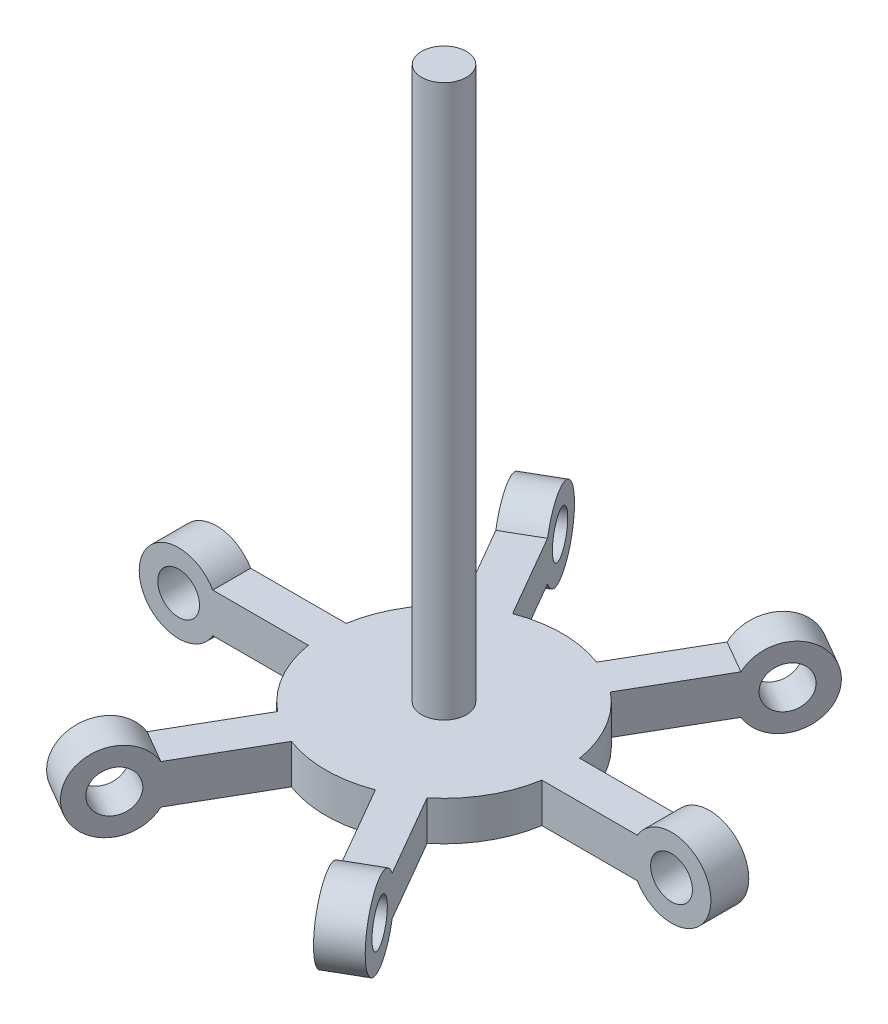
SolidWorks part; units mm, degrees
material "6061 合金"
ref_plane "前视基准面" through (0, 0, 0) normal (0, 0, 1) x (1, 0, 0)
ref_plane "上视基准面" through (0, 0, 0) normal (0, 1, 0) x (1, 0, 0)
ref_plane "右视基准面" through (0, 0, 0) normal (1, 0, 0) x (0, 0, -1)
sketch "草图1" plane through (0, 0, 0) normal (0, 1, 0) x (1, 0, 0)
  circle A0 centre (0, 0) radius 30
  dimension "D1" = 60
extrude "凸台-拉伸1" add sketch "草图1" along normal mid plane 10
sketch "草图2" plane through (0, 0, 0) normal (0, 1, 0) x (1, 0, 0)
  line L0 (0, 0) -> (45, 0) construction
  line L2 (70, -4.8) -> (20, -4.8)
  line L3 (70, -4.8) -> (70, 4.8)
  line L4 (70, 4.8) -> (20, 4.8)
  line L5 (20, -4.8) -> (20, 4.8)
  line L6 (70, -4.8) -> (20, 4.8) construction
  line L7 (70, 4.8) -> (20, -4.8) construction
  dimension "D1" = 70
  dimension "D2" = 9.6
  dimension "D3" = 50
extrude "凸台-拉伸2" add sketch "草图2" along normal mid plane 10
sketch "草图3" plane through (0, 0, 4.8) normal (0, 0, 1) x (1, 0, 0)
  line L0 (70, 0) -> (62.5, 0) construction
  line L1 (70, 5) -> (70, -5) construction
  circle A0 centre (62.5, 0) radius 10
  dimension "D2" = 20
  dimension "D1" = 7.5
extrude "凸台-拉伸3" add sketch "草图3" against normal blind 9.6
sketch "草图4" plane through (0, 0, 4.8) normal (0, 0, 1) x (1, 0, 0)
  circle A0 centre (62.5, 0) radius 5.3
  dimension "D1" = 10.6
extrude "切除-拉伸1" cut sketch "草图4" against normal blind 10
pattern_circular "阵列(圆周)1" count 6 over 360 about axis through (0, 5, 0) along (0, -1, 0) of "凸台-拉伸2", "凸台-拉伸3", "切除-拉伸1"
sketch "草图5" plane through (0, 5, 0) normal (0, 1, 0) x (1, 0, 0)
  circle A0 centre (0, 0) radius 5.7
  dimension "D1" = 11.4
extrude "细杆_直径11.4_长度140" add sketch "草图5" along normal blind 140
